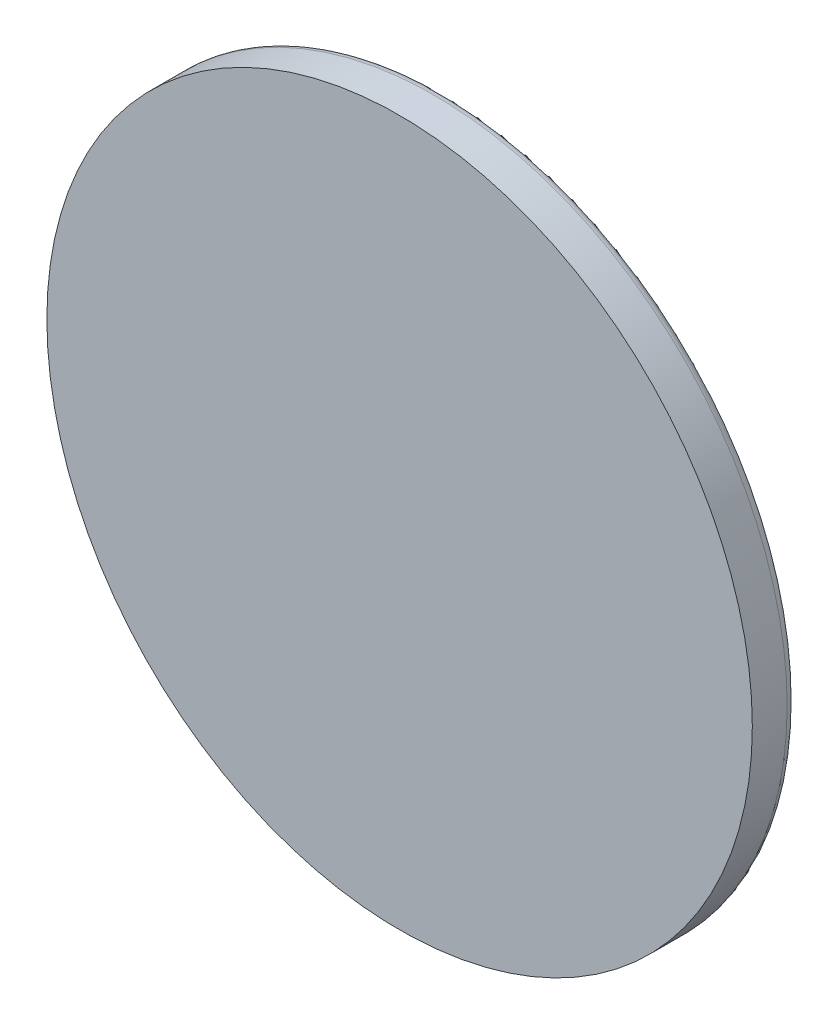
SolidWorks part; units mm, degrees
ref_plane "Front Plane" through (0, 0, 0) normal (0, 0, 1) x (1, 0, 0)
ref_plane "Top Plane" through (0, 0, 0) normal (0, 1, 0) x (1, 0, 0)
ref_plane "Right Plane" through (0, 0, 0) normal (1, 0, 0) x (0, 0, -1)
sketch "Sketch1" plane through (0, 0, 0) normal (0, 0, 1) x (1, 0, 0)
  circle A0 centre (-43, 22.86) radius 19.05 construction
  circle A1 centre (-43, 22.86) radius 19.05 construction
  circle A2 centre (-43, 22.86) radius 18.65
  dimension "D1" = 0.4
extrude "Boss-Extrude1" add sketch "Sketch1" against normal blind 2.3495
sketch "Sketch4" plane through (0, 0, -2.3495) normal (0, 0, -1) x (-1, 0, 0)
  circle A0 centre (43, 22.86) radius 18.65 construction
  circle A1 centre (43, 22.86) radius 18.65 construction
  circle A2 centre (43, 22.86) radius 12.446
  dimension "D1" = 24.892
extrude "Boss-Extrude2" add sketch "Sketch4" along normal up to surface (4.0005 mm away)
sketch "Sketch5" plane through (0, 0, -6.35) normal (0, 0, -1) x (-1, 0, 0)
  line L0 (55.446, 22.86) -> (30.554, 22.86) construction
  line L1 (43, 22.86) -> (43, 35.306) construction
  circle A0 centre (43, 22.86) radius 12.446 construction
  circle A1 centre (43, 22.86) radius 12.446 construction
  circle A2 centre (43, 29.083) radius 3.3275
  circle A3 centre (43, 16.637) radius 3.3275
  dimension "D1" = 6.655
extrude "Cut-Extrude1" cut sketch "Sketch5" against normal offset from surface (5.85 mm away) 0.5 up to face at (-24.35, 22.86, 0)
fillet "Fillet1" radius 0.508 3 edges at (-24.35, 22.86, -2.3495) (-30.554, 22.86, -2.3495) (-55.446, 22.86, -6.35)
